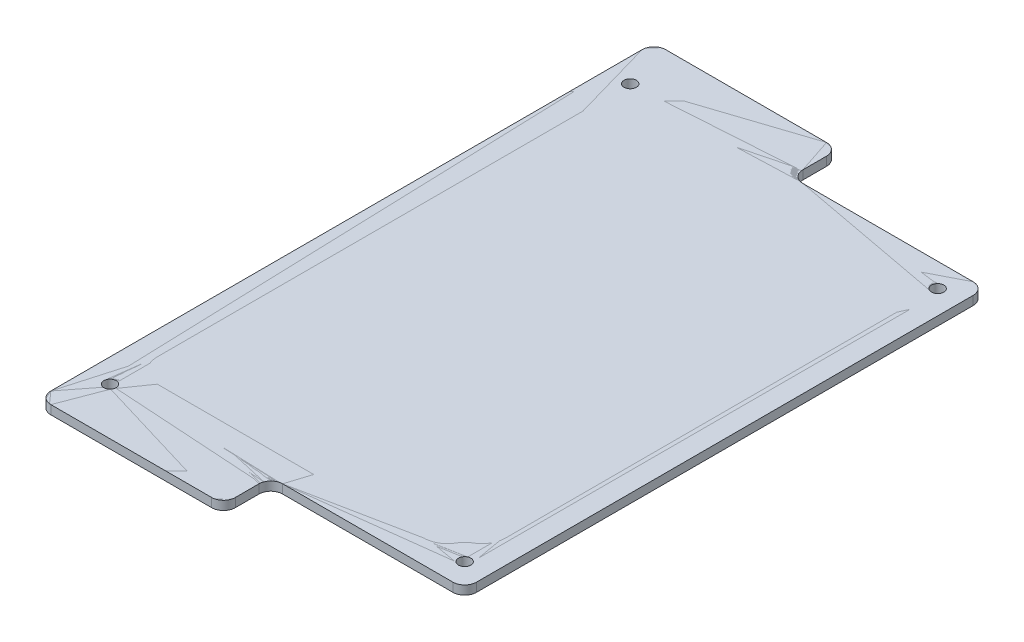
SolidWorks part; units mm, degrees
material "Balsa"
ref_plane "Front Plane" through (0, 0, 0) normal (0, 0, 1) x (1, 0, 0)
ref_plane "Top Plane" through (0, 0, 0) normal (0, 1, 0) x (1, 0, 0)
ref_plane "Right Plane" through (0, 0, 0) normal (1, 0, 0) x (0, 0, -1)
sketch "Sketch1" plane through (0, 0, 0) normal (0, 1, 0) x (1, 0, 0)
  line L1 (-101.6, 165.1) -> (101.6, 165.1)
  line L2 (-101.6, 165.1) -> (-101.6, -165.1)
  line L3 (-101.6, -165.1) -> (101.6, -165.1)
  line L4 (101.6, 165.1) -> (101.6, -165.1)
  line L5 (-101.6, 165.1) -> (101.6, -165.1) construction
  line L6 (-101.6, -165.1) -> (101.6, 165.1) construction
  point P0 (0, 0)
  dimension "D1" = 330.2
  dimension "D2" = 203.2
extrude "Base" add sketch "Sketch1" along normal blind 4.7625
sketch "Sketch2" plane through (0, 4.7625, 0) normal (0, 1, 0) x (1, 0, 0)
  line L0 (101.6, -165.1) -> (101.6, 165.1) construction
  line L1 (-88.9, 139.7) -> (88.9, 139.7) construction
  line L2 (-88.9, 139.7) -> (-88.9, -139.7) construction
  line L3 (-88.9, -139.7) -> (88.9, -139.7) construction
  line L4 (88.9, 139.7) -> (88.9, -139.7) construction
  line L5 (-88.9, 139.7) -> (88.9, -139.7) construction
  line L6 (-88.9, -139.7) -> (88.9, 139.7) construction
  line L7 (-101.6, -165.1) -> (101.6, -165.1) construction
  line L9 (-88.9, 127) -> (88.9, 127) construction
  line L10 (-88.9, 127) -> (-88.9, -127) construction
  line L11 (-88.9, -127) -> (88.9, -127) construction
  line L12 (88.9, 127) -> (88.9, -127) construction
  line L13 (-88.9, 127) -> (88.9, -127) construction
  line L14 (-88.9, -127) -> (88.9, 127) construction
  circle A1 centre (-88.9, 139.7) radius 3.302
  circle A3 centre (-88.9, -139.7) radius 3.302
  circle A4 centre (88.9, -127) radius 3.302
  circle A5 centre (88.9, 127) radius 3.302
  point P0 (0, 0)
  point P14 (0, 0)
  dimension "D1" = 6.604
  dimension "D2" = 12.7
  dimension "D3" = 25.4
  dimension "D4" = 254
extrude "Holes" cut sketch "Sketch2" against normal through all both and the other way through all
sketch "Sketch3" plane through (0, 4.7625, 0) normal (0, 1, 0) x (1, 0, 0)
  line L0 (101.6, 165.1) -> (-101.6, 165.1) construction
  line L1 (-2.54, 165.1) -> (78.74, 165.1) construction
  line L2 (-2.54, 165.1) -> (-2.54, 139.7) construction
  line L3 (-2.54, 139.7) -> (78.74, 139.7) construction
  line L4 (78.74, 165.1) -> (78.74, 139.7) construction
  line L5 (38.1, 139.7) -> (38.1, 165.1) construction
  line L6 (-2.54, 152.4) -> (78.74, 152.4) construction
  line L7 (-101.6, -165.1) -> (101.6, -165.1) construction
  line L8 (-2.54, -165.1) -> (78.74, -165.1) construction
  line L9 (-2.54, -165.1) -> (-2.54, -139.7) construction
  line L10 (-2.54, -139.7) -> (78.74, -139.7) construction
  line L11 (78.74, -165.1) -> (78.74, -139.7) construction
  line L12 (38.1, -139.7) -> (38.1, -165.1) construction
  line L13 (-2.54, -152.4) -> (78.74, -152.4) construction
  line L14 (101.6, -165.1) -> (101.6, 165.1) construction
  line L15 (101.6, 165.1) -> (127, 165.1) construction
  line L16 (101.6, 165.1) -> (101.6, -165.1) construction
  line L17 (101.6, -165.1) -> (127, -165.1) construction
  line L18 (127, 165.1) -> (127, -165.1) construction
  line L19 (114.3, -165.1) -> (114.3, 165.1) construction
  line L20 (101.6, 0) -> (127, 0) construction
  line L22 (-2.54, 139.7) -> (101.6, 139.7)
  line L23 (-2.54, 139.7) -> (-2.54, 165.1)
  line L24 (-2.54, 165.1) -> (101.6, 165.1)
  line L25 (101.6, 139.7) -> (101.6, 165.1)
  line L26 (49.53, 165.1) -> (49.53, 139.7) construction
  line L27 (-2.54, 152.4) -> (101.6, 152.4) construction
  line L28 (-2.54, -139.7) -> (101.6, -139.7)
  line L29 (-2.54, -139.7) -> (-2.54, -165.1)
  line L30 (-2.54, -165.1) -> (101.6, -165.1)
  line L31 (101.6, -139.7) -> (101.6, -165.1)
  line L32 (49.53, -165.1) -> (49.53, -139.7) construction
  line L33 (-2.54, -152.4) -> (101.6, -152.4) construction
  point P130 (38.1, -152.4)
  point P165 (114.3, 0)
  point P188 (38.1, 152.4)
  point P221 (49.53, -152.4)
  point P239 (49.53, 152.4)
  dimension "D1" = 25.4
  dimension "D2" = 81.28
  dimension "D3" = 25.4
  dimension "D4" = 76.2
extrude "Sus Tab Cutout" cut sketch "Sketch3" against normal through all both and the other way through all
sketch "Sketch4" plane through (0, 4.7625, 0) normal (0, 1, 0) x (1, 0, 0)
  line L0 (101.6, -139.7) -> (101.6, 139.7) construction
  line L1 (-88.9, 127) -> (88.9, 127) construction
  line L2 (-88.9, 127) -> (-88.9, -127) construction
  line L3 (-88.9, -127) -> (88.9, -127) construction
  line L4 (88.9, 127) -> (88.9, -127) construction
  line L5 (-88.9, 127) -> (88.9, -127) construction
  line L6 (-88.9, -127) -> (88.9, 127) construction
  line L8 (88.9, 114.3) -> (88.9, -114.3)
  line L9 (76.2, -127) -> (-88.9, -127)
  line L10 (-88.9, -127) -> (-88.9, 127)
  line L11 (-88.9, 127) -> (76.2, 127)
  line L12 (101.6, -139.7) -> (-2.54, -139.7) construction
  arc A0 (76.2, 127) -> (88.9, 114.3) centre (88.9, 127) ccw
  arc A1 (76.2, -127) -> (88.9, -114.3) centre (88.9, -127) cw
  point P0 (0, 0)
  dimension "D3" = 12.7
  dimension "D1" = 12.7
  dimension "D2" = 12.7
extrude "Inner Cutout" cut sketch "Sketch4" against normal through all both and the other way through all
fillet "Fillet1" radius 6.35 8 edges at (-101.6, 2.3813, -165.1) (-101.6, 2.3813, 165.1) (101.6, 2.3812, 139.7) (101.6, 2.3812, -139.7) (-2.54, 2.3812, 165.1) (-2.54, 2.3812, 139.7) (-2.54, 2.3812, -165.1) (-2.54, 2.3812, -139.7)
fillet "Fillet2" radius 12.7 6 edges at (88.9, 2.3812, 114.3) (76.2, 2.3812, 127) (-88.9, 2.3812, 127) (-88.9, 2.3813, -127) (88.9, 2.3812, -114.3) (76.2, 2.3812, -127)
sketch "Sketch6" plane through (0, 4.7625, 0) normal (0, 1, 0) x (1, 0, 0)
  line L8 (-2.54, -158.75) -> (-2.54, -146.05)
  line L9 (-2.54, -158.75) -> (-2.54, -146.05)
  line L10 (3.81, -139.7) -> (95.25, -139.7)
  line L11 (3.81, -139.7) -> (95.25, -139.7)
  line L12 (95.25, 139.7) -> (3.81, 139.7)
  line L13 (-95.25, -165.1) -> (-8.89, -165.1)
  line L14 (101.6, -133.35) -> (101.6, 133.35)
  line L15 (-8.89, 165.1) -> (-95.25, 165.1)
  line L16 (95.25, 139.7) -> (3.81, 139.7)
  line L17 (-2.54, 146.05) -> (-2.54, 158.75)
  line L18 (-2.54, 146.05) -> (-2.54, 158.75)
  line L20 (-101.6, 158.75) -> (-101.6, -158.75)
  line L25 (-95.25, -165.1) -> (-8.89, -165.1)
  line L26 (101.6, -133.35) -> (101.6, 133.35)
  line L27 (-8.89, 165.1) -> (-95.25, 165.1)
  line L32 (-101.6, 158.75) -> (-101.6, -158.75)
  circle A0 centre (-88.9, -139.7) radius 3.302 construction
  circle A1 centre (88.9, -127) radius 3.302 construction
  circle A2 centre (88.9, 127) radius 3.302 construction
  circle A3 centre (-88.9, 139.7) radius 3.302 construction
  circle A4 centre (-88.9, -139.7) radius 3.302
  circle A5 centre (88.9, -127) radius 3.302
  circle A6 centre (88.9, 127) radius 3.302
  circle A7 centre (-88.9, 139.7) radius 3.302
  arc A16 (95.25, -139.7) -> (101.6, -133.35) centre (95.25, -133.35) ccw
  arc A17 (95.25, -139.7) -> (101.6, -133.35) centre (95.25, -133.35) ccw
  arc A18 (101.6, 133.35) -> (95.25, 139.7) centre (95.25, 133.35) ccw
  arc A19 (-95.25, 165.1) -> (-101.6, 158.75) centre (-95.25, 158.75) ccw
  arc A20 (-101.6, -158.75) -> (-95.25, -165.1) centre (-95.25, -158.75) ccw
  arc A21 (101.6, 133.35) -> (95.25, 139.7) centre (95.25, 133.35) ccw
  arc A22 (-2.54, 146.05) -> (3.81, 139.7) centre (3.81, 146.05) ccw
  arc A23 (-2.54, 146.05) -> (3.81, 139.7) centre (3.81, 146.05) ccw
  arc A31 (-95.25, 165.1) -> (-101.6, 158.75) centre (-95.25, 158.75) ccw
  arc A32 (-101.6, -158.75) -> (-95.25, -165.1) centre (-95.25, -158.75) ccw
  arc A36 (-2.54, 158.75) -> (-8.89, 165.1) centre (-8.89, 158.75) ccw
  arc A37 (-2.54, 158.75) -> (-8.89, 165.1) centre (-8.89, 158.75) ccw
  arc A38 (-8.89, -165.1) -> (-2.54, -158.75) centre (-8.89, -158.75) ccw
  arc A39 (-8.89, -165.1) -> (-2.54, -158.75) centre (-8.89, -158.75) ccw
  arc A40 (3.81, -139.7) -> (-2.54, -146.05) centre (3.81, -146.05) ccw
  arc A41 (3.81, -139.7) -> (-2.54, -146.05) centre (3.81, -146.05) ccw
  dimension "D1" = 0
surface "Surface-Plane1" sketch "Sketch6"
sketch "Sketch9" plane through (0, 0, 0) normal (0, -1, 0) x (1, 0, 0)
  line L8 (-2.54, 146.05) -> (-2.54, 158.75)
  line L9 (-2.54, 146.05) -> (-2.54, 158.75)
  line L10 (95.25, 139.7) -> (3.81, 139.7)
  line L11 (95.25, 139.7) -> (3.81, 139.7)
  line L12 (3.81, -139.7) -> (95.25, -139.7)
  line L13 (3.81, -139.7) -> (95.25, -139.7)
  line L14 (-2.54, -158.75) -> (-2.54, -146.05)
  line L15 (-8.89, 165.1) -> (-95.25, 165.1)
  line L16 (101.6, -133.35) -> (101.6, 133.35)
  line L17 (-95.25, -165.1) -> (-8.89, -165.1)
  line L18 (-2.54, -158.75) -> (-2.54, -146.05)
  line L22 (-101.6, 158.75) -> (-101.6, -158.75)
  line L27 (-8.89, 165.1) -> (-95.25, 165.1)
  line L28 (101.6, -133.35) -> (101.6, 133.35)
  line L29 (-95.25, -165.1) -> (-8.89, -165.1)
  line L34 (-101.6, 158.75) -> (-101.6, -158.75)
  circle A1 centre (-88.9, -139.7) radius 3.302
  circle A2 centre (-88.9, -139.7) radius 3.302
  circle A3 centre (88.9, -127) radius 3.302
  circle A4 centre (88.9, -127) radius 3.302
  circle A5 centre (88.9, 127) radius 3.302
  circle A6 centre (88.9, 127) radius 3.302
  circle A7 centre (-88.9, 139.7) radius 3.302
  circle A8 centre (-88.9, 139.7) radius 3.302
  arc A16 (-2.54, 158.75) -> (-8.89, 165.1) centre (-8.89, 158.75) ccw
  arc A17 (-2.54, 158.75) -> (-8.89, 165.1) centre (-8.89, 158.75) ccw
  arc A18 (-2.54, 146.05) -> (3.81, 139.7) centre (3.81, 146.05) ccw
  arc A19 (-2.54, 146.05) -> (3.81, 139.7) centre (3.81, 146.05) ccw
  arc A20 (101.6, 133.35) -> (95.25, 139.7) centre (95.25, 133.35) ccw
  arc A21 (101.6, 133.35) -> (95.25, 139.7) centre (95.25, 133.35) ccw
  arc A22 (95.25, -139.7) -> (101.6, -133.35) centre (95.25, -133.35) ccw
  arc A23 (95.25, -139.7) -> (101.6, -133.35) centre (95.25, -133.35) ccw
  arc A24 (3.81, -139.7) -> (-2.54, -146.05) centre (3.81, -146.05) ccw
  arc A25 (3.81, -139.7) -> (-2.54, -146.05) centre (3.81, -146.05) ccw
  arc A26 (-8.89, -165.1) -> (-2.54, -158.75) centre (-8.89, -158.75) ccw
  arc A27 (-8.89, -165.1) -> (-2.54, -158.75) centre (-8.89, -158.75) ccw
  arc A29 (-101.6, -158.75) -> (-95.25, -165.1) centre (-95.25, -158.75) ccw
  arc A30 (-95.25, 165.1) -> (-101.6, 158.75) centre (-95.25, 158.75) ccw
  arc A41 (-101.6, -158.75) -> (-95.25, -165.1) centre (-95.25, -158.75) ccw
  arc A42 (-95.25, 165.1) -> (-101.6, 158.75) centre (-95.25, 158.75) ccw
  dimension "D1" = 0
  dimension "D2" = 0
  dimension "D3" = 0
  dimension "D4" = 0
  dimension "D5" = 0
surface "Surface-Plane2" sketch "Sketch9"
